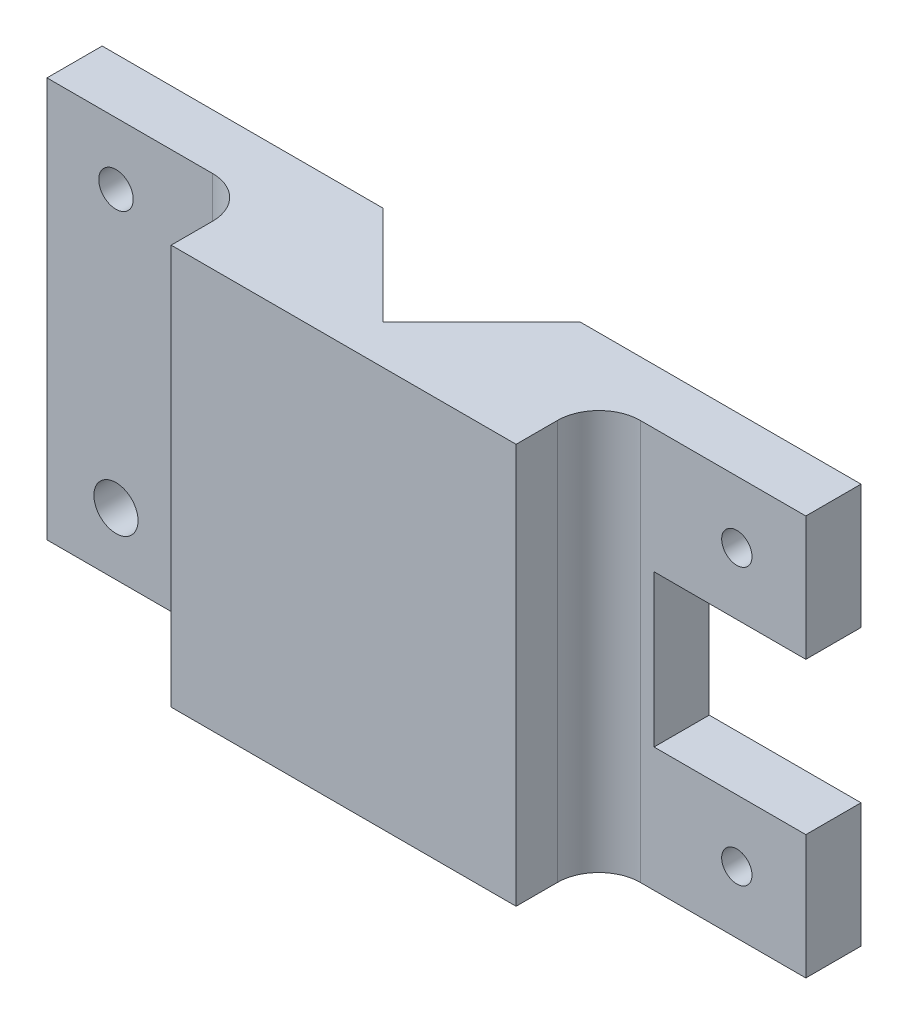
SolidWorks part; units mm, degrees
ref_plane "Front Plane" through (0, 0, 0) normal (0, 0, 1) x (1, 0, 0)
ref_plane "Top Plane" through (0, 0, 0) normal (0, 1, 0) x (1, 0, 0)
ref_plane "Right Plane" through (0, 0, 0) normal (1, 0, 0) x (0, 0, -1)
sketch "Sketch1" plane through (0, 0, 0) normal (0, 1, 0) x (1, 0, 0)
  line L5 (-7.1317, 0) -> (-27.5, 0)
  line L12 (7.1317, 0) -> (27.5, 0)
  line L13 (27.5, 0) -> (27.5, -4)
  line L14 (27.5, -4) -> (12.5, -4)
  line L15 (12.5, -4) -> (12.5, -10)
  line L16 (12.5, -10) -> (-12.5, -10)
  line L17 (-27.5, 0) -> (-27.5, -4)
  line L18 (-27.5, -4) -> (-12.5, -4)
  line L19 (-12.5, -4) -> (-12.5, -10)
  line L20 (-7.1317, 0) -> (0, -7.1317)
  line L21 (0, -7.1317) -> (7.1317, 0)
  circle A2 centre (0, 1.6718) radius 6.225 construction
  circle A3 centre (0, 1) radius 5.75 construction
  point P0 (0, 0)
  point P14 (0, 3.5795)
  point P18 (0, 0)
  point P19 (0, 1.8068)
  point P20 (0, -7.6404)
  point P21 (0, -6.9166)
  point P22 (0, -7.0757)
  dimension "D5" = 25
  dimension "D9" = 12.45
  dimension "D10" = 11.5
  dimension "D1" = 15
  dimension "D2" = 15
  dimension "D3" = 1
  dimension "D4" = 1.6718
  dimension "D6" = 4
  dimension "D7" = 10
extrude "Boss-Extrude1" add sketch "Sketch1" along normal mid plane 29
sketch "Sketch4" plane through (0, 0, 4) normal (0, 0, 1) x (1, 0, 0)
  line L0 (27.5, 5.5) -> (16.5, 5.5)
  line L1 (27.5, 14.5) -> (27.5, -14.5) construction
  line L2 (16.5, 5.5) -> (16.5, -5.5)
  line L3 (16.5, -5.5) -> (27.5, -5.5)
  line L4 (0, 0) -> (27.5, 0) construction
  line L5 (12.5, -14.5) -> (27.5, -14.5) construction
  line L6 (12.5, 14.5) -> (27.5, 14.5) construction
  line L7 (27.5, 5.5) -> (27.5, -5.5)
  circle A0 centre (22.5, 10) radius 1.1
  circle A1 centre (22.5, -10) radius 1.1
  dimension "D1" = 2.2
  dimension "D2" = 2.2
  dimension "D3" = 9
  dimension "D4" = 20
  dimension "D5" = 10
  dimension "D6" = 9
  dimension "D7" = 11
  dimension "D8" = 5
extrude "Cut-Extrude2" cut sketch "Sketch4" against normal through all and the other way through all
sketch "Sketch5" plane through (0, 0, 4) normal (0, 0, 1) x (1, 0, 0)
  line L4 (-27.5, 0) -> (0, 0) construction
  line L5 (-27.5, 14.5) -> (-27.5, -14.5) construction
  circle A0 centre (-22.5, 10) radius 1.25
  circle A1 centre (-22.5, -10) radius 1.6
  dimension "D1" = 2.5
  dimension "D2" = 3.2
  dimension "D3" = 5
  dimension "D4" = 20
  dimension "D5" = 10
extrude "Cut-Extrude3" cut sketch "Sketch5" against normal through all
fillet "Fillet1" radius 3 2 edges at (12.5, 0, 4) (-12.5, 0, 4)
